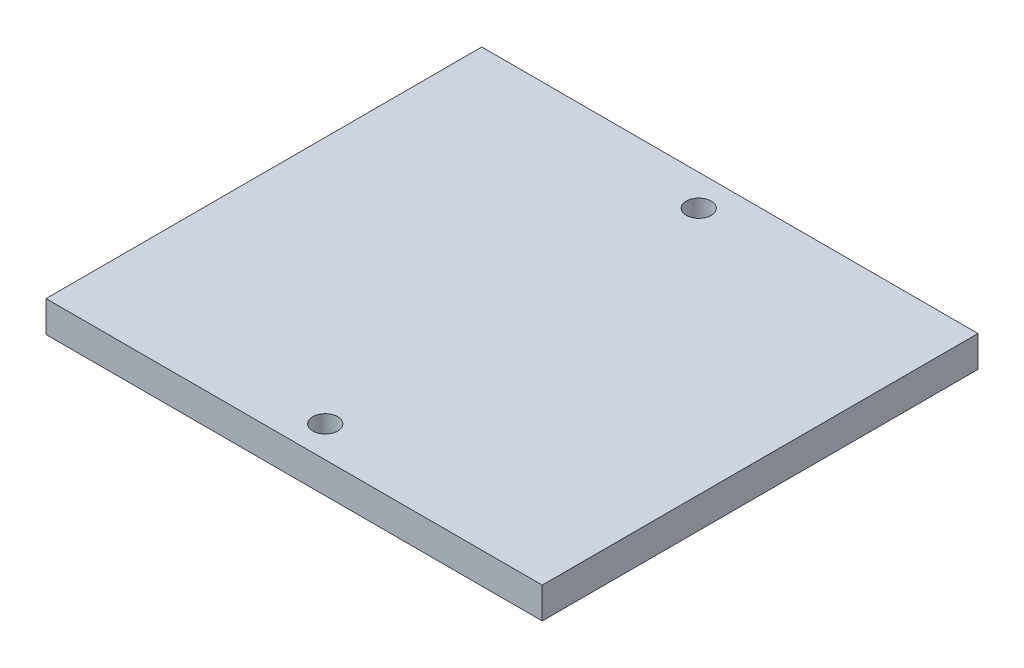
SolidWorks part; units mm, degrees
material "6061 Alloy"
ref_plane "Front" through (0, 0, 0) normal (0, 0, 1) x (1, 0, 0)
ref_plane "Top" through (0, 0, 0) normal (0, 1, 0) x (1, 0, 0)
ref_plane "Right" through (0, 0, 0) normal (1, 0, 0) x (0, 0, -1)
sketch "Sketch1" plane through (0, 0, 0) normal (0, 1, 0) x (1, 0, 0)
  line L1 (-50.6187, -44.45) -> (50.6188, -44.45)
  line L2 (-50.6187, -44.45) -> (-50.6187, 44.45)
  line L3 (-50.6187, 44.45) -> (50.6188, 44.45)
  line L4 (50.6188, -44.45) -> (50.6188, 44.45)
  line L5 (-50.6187, -44.45) -> (50.6188, 44.45) construction
  line L6 (-50.6187, 44.45) -> (50.6188, -44.45) construction
  point P0 (0, 0)
  dimension "D1" = 101.2375
  dimension "D2" = 88.9
extrude "Boss-Extrude1" add sketch "Sketch1" along normal blind 6.35
sketch "Sketch2" plane through (0, 6.35, 0) normal (0, 1, 0) x (1, 0, 0)
  line L0 (0, 44.45) -> (0, 38.1) construction
  line L1 (50.6188, 44.45) -> (-50.6187, 44.45) construction
  line L2 (-50.6187, 0) -> (50.6188, 0) construction
  line L3 (-50.6187, 44.45) -> (-50.6187, -44.45) construction
  line L4 (50.6188, -44.45) -> (50.6188, 44.45) construction
  circle A0 centre (0, 38.1) radius 2.54
  circle A1 centre (0, -38.1) radius 2.54
  dimension "D2" = 5.08
  dimension "D1" = 6.35
extrude "Cut-Extrude1" cut sketch "Sketch2" against normal through all
